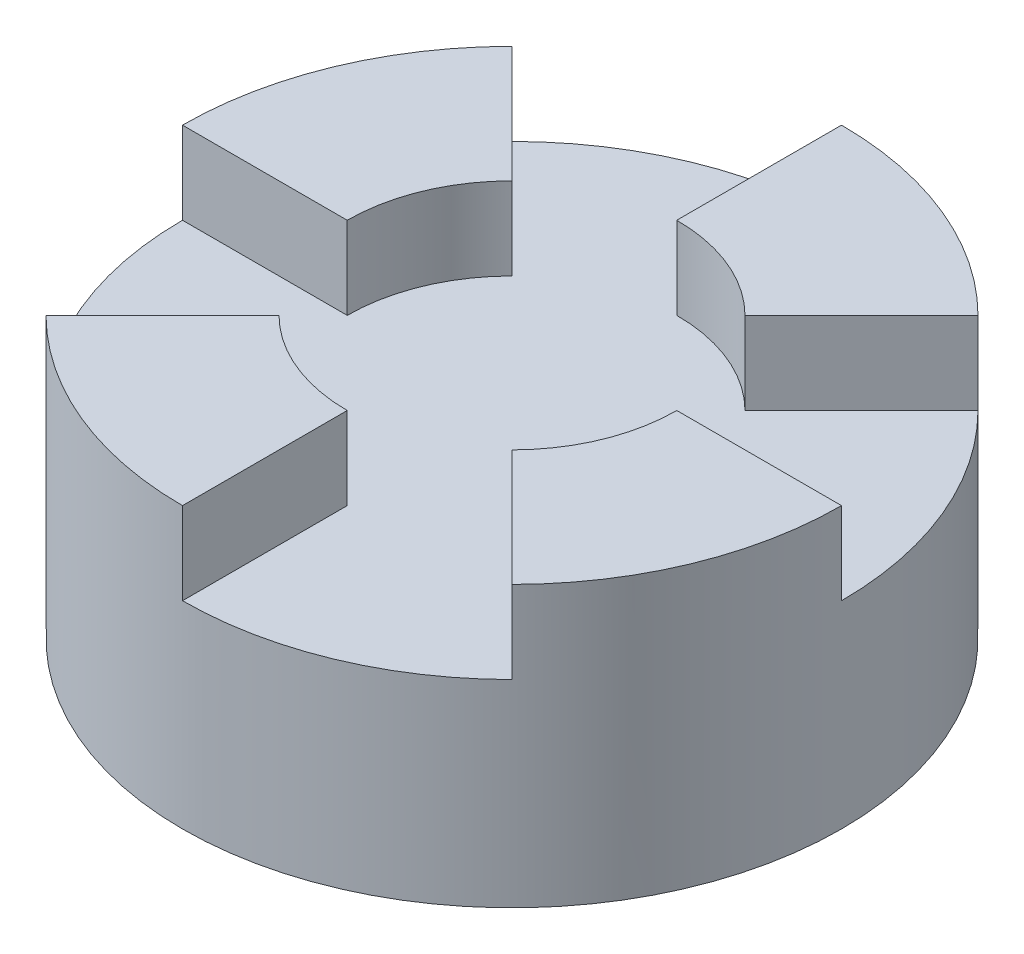
SolidWorks part; units mm, degrees
ref_plane "Front Plane" through (0, 0, 0) normal (0, 0, 1) x (1, 0, 0)
ref_plane "Top Plane" through (0, 0, 0) normal (0, 1, 0) x (1, 0, 0)
ref_plane "Right Plane" through (0, 0, 0) normal (1, 0, 0) x (0, 0, -1)
sketch "Sketch1" plane through (0, 0, 0) normal (0, 1, 0) x (1, 0, 0)
  circle A0 centre (0, 0) radius 20
  dimension "D1" = 40
extrude "Extrude (Mechanism Part 1)" add sketch "Sketch1" along normal blind 17
sketch "Sketch2" plane through (0, 17, 0) normal (0, 1, 0) x (1, 0, 0)
  line L0 (0, 20) -> (0, -20)
  line L1 (-20, 0) -> (20, 0)
  line L2 (0, 0) -> (14.1421, 14.1421)
  line L3 (0, 0) -> (14.1421, -14.1421)
  line L4 (0, 0) -> (-14.1421, -14.1421)
  line L5 (0, 0) -> (-14.1421, 14.1421)
  circle A0 centre (0, 0) radius 10
  circle A1 centre (0, 0) radius 20 construction
  circle M3 centre (0, 0) radius 20
  dimension "D1" = 20
  dimension "D2" = 45
extrude "Cut (Mechanism Part 1)" cut sketch "Sketch2" against normal blind 5 contours A0 L0 L5 M3 | A0 L1 L2 M3 | A0 L0 L3 M3 | A0 L1 L4 M3 | L1 A0 L4 | L5 A0 L1 | L0 A0 L5 | L2 A0 L0 | L1 A0 L2 | L3 A0 L1 | L0 A0 L3 | L4 A0 L0
sketch "Sketch3" plane through (0, 12, 0) normal (0, 1, 0) x (1, 0, 0)
  circle A0 centre (0, 0) radius 1
  dimension "D1" = 2
